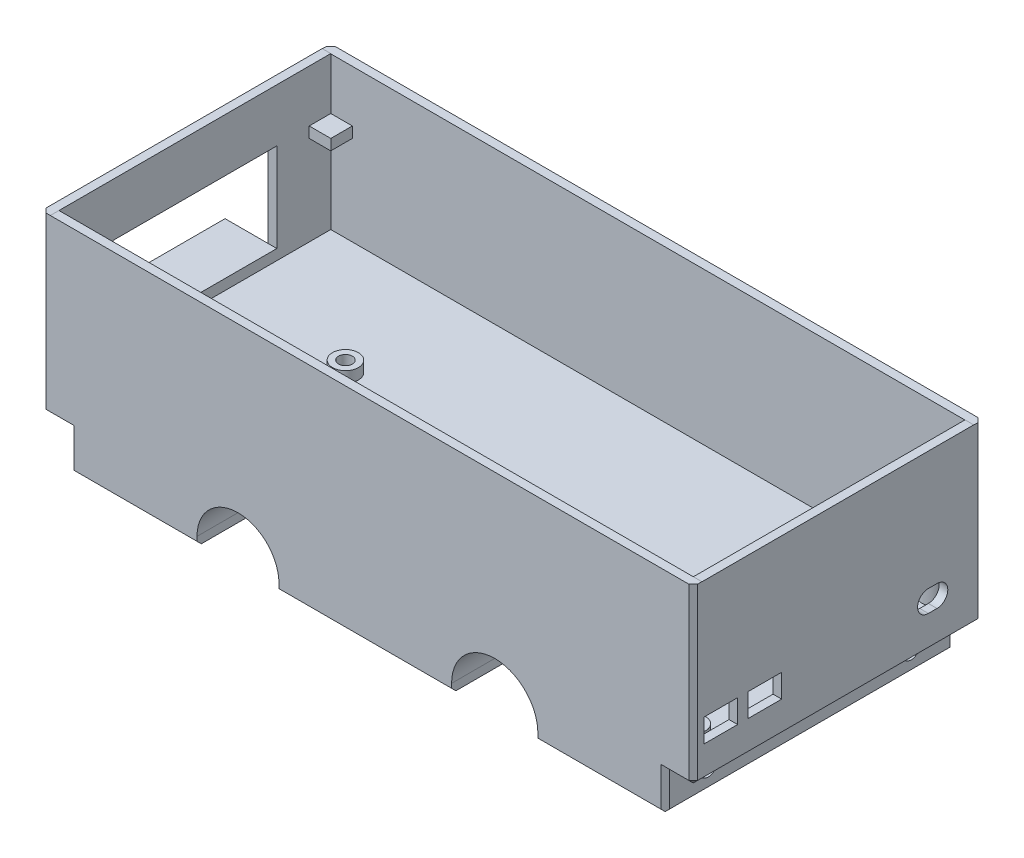
SolidWorks part; units mm, degrees
ref_plane "Ebene vorne" through (0, 0, 0) normal (0, 0, 1) x (1, 0, 0)
ref_plane "Ebene oben" through (0, 0, 0) normal (0, 1, 0) x (1, 0, 0)
ref_plane "Ebene rechts" through (0, 0, 0) normal (1, 0, 0) x (0, 0, -1)
sketch "Skizze1" plane through (0, 0, 0) normal (0, 0, 1) x (1, 0, 0)
  line L0 (13.4016, 0) -> (13.4016, -2)
  line L1 (13.4016, -2) -> (53.4016, -2)
  line L2 (53.4016, -2) -> (53.4016, 0)
  line L3 (51.4016, 0) -> (15.4882, 0)
  line L4 (-5.5984, 0) -> (-5.5984, -2)
  line L5 (-5.5984, -2) -> (-41.5984, -2)
  line L6 (-41.5984, -2) -> (-41.5984, 0)
  line L7 (-41.5984, 0) -> (-7.6851, 0)
  line L8 (73.4016, 0) -> (73.4016, -2)
  line L9 (73.4016, -2) -> (109.4016, -2)
  line L10 (75.4016, 0) -> (109.4016, 0)
  line L11 (109.4016, 0) -> (109.4016, -2)
  arc A0 (13.4016, 0) -> (-5.5984, 0) centre (3.9016, -3.1225) ccw
  arc A1 (73.4016, 0) -> (53.4016, 0) centre (63.4016, 0) ccw
  arc A2 (15.4882, 0) -> (-7.6851, 0) centre (3.9016, -3.1225) ccw
  arc A3 (75.4016, 0) -> (51.4016, 0) centre (63.4016, 0) ccw
  dimension "D2" = 10
  dimension "D3" = 12
  dimension "D4" = 10
  dimension "D5" = 12
  dimension "D6" = 40
  dimension "D7" = 2
  dimension "D8" = 2
  dimension "D9" = 2
  dimension "D10" = 2
  dimension "D11" = 2
  dimension "D12" = 2
  dimension "D13" = 36
  dimension "D14" = 2
  dimension "D15" = 36
extrude "Aufsatz-Linear austragen1" add sketch "Skizze1" along normal blind 67
sketch "Skizze3" plane through (0, 0, 0) normal (0, 1, 0) x (1, 0, 0)
  line L0 (109.4016, -67) -> (109.4016, 0) construction
  line L1 (-41.5984, 0) -> (109.4016, 0)
  line L2 (-41.5984, 0) -> (-41.5984, -2)
  line L3 (-41.5984, -2) -> (109.4016, -2)
  line L4 (109.4016, 0) -> (109.4016, -2)
  dimension "D1" = 2
extrude "Aufsatz-Linear austragen2" add sketch "Skizze3" along normal blind 47.3424
sketch "Skizze4" plane through (0, 0, 0) normal (0, 1, 0) x (1, 0, 0)
  line L0 (-7.6851, -67) -> (-41.5984, -67) construction
  line L1 (-41.5984, -2) -> (-39.5984, -2)
  line L2 (-41.5984, -2) -> (-41.5984, -67)
  line L3 (-41.5984, -67) -> (-39.5984, -67)
  line L4 (-39.5984, -2) -> (-39.5984, -67)
  dimension "D1" = 2
extrude "Aufsatz-Linear austragen3" add sketch "Skizze4" along normal blind 47.3981
sketch "Skizze6" plane through (0, 0, 0) normal (0, 1, 0) x (1, 0, 0)
  line L0 (109.4016, -67) -> (109.4016, -2) construction
  line L1 (-39.5984, -67) -> (109.4016, -67)
  line L2 (-39.5984, -67) -> (-39.5984, -65)
  line L3 (-39.5984, -65) -> (109.4016, -65)
  line L4 (109.4016, -67) -> (109.4016, -65)
  dimension "D1" = 2
extrude "Aufsatz-Linear austragen4" add sketch "Skizze6" along normal blind 47.401
sketch "Skizze7" plane through (0, 0, 0) normal (0, 1, 0) x (1, 0, 0)
  line L0 (75.4016, -2) -> (109.4016, -2) construction
  line L1 (109.4016, -65) -> (107.4016, -65)
  line L2 (109.4016, -65) -> (109.4016, -2)
  line L3 (109.4016, -2) -> (107.4016, -2)
  line L4 (107.4016, -65) -> (107.4016, -2)
  dimension "D1" = 2
extrude "Aufsatz-Linear austragen5" add sketch "Skizze7" along normal blind 47.3732
sketch "Skizze20" plane through (0, 0, 2) normal (0, 0, 1) x (1, 0, 0)
  line L0 (107.4016, 47.3424) -> (107.4016, 0) construction
  line L1 (107.4016, 12.0802) -> (-39.5984, 12.0802)
  line L2 (107.4016, 12.0802) -> (107.4016, 0)
  line L3 (107.4016, 0) -> (-39.5984, 0)
  line L4 (-39.5984, 12.0802) -> (-39.5984, 0)
extrude "Aufsatz-Linear austragen6" add sketch "Skizze20" along normal blind 63
sketch "Skizze8" plane through (0, 0, 67) normal (0, 0, 1) x (1, 0, 0)
  line L1 (-5.5984, 0) -> (13.4016, 0) construction
  line L2 (53.4016, 0) -> (73.4016, 0) construction
  line L3 (53.4016, -2) -> (53.4016, 0) construction
  line L4 (53.4016, 0) -> (73.4016, 0)
  line L5 (-5.5984, 0) -> (13.4016, 0)
  arc A2 (13.4016, 0) -> (-5.5984, 0) centre (3.9016, 0) ccw
  arc A3 (73.4016, 0) -> (53.4016, 0) centre (63.4016, 0) ccw
extrude "Schnitt-Linear austragen1" cut sketch "Skizze8" against normal through all
sketch "Skizze23" plane through (109.4016, 0, 0) normal (1, 0, 0) x (0, 0, -1)
  line L0 (-67, -2) -> (-67, 47.401) construction
  line L1 (-64.5, 19.9802) -> (-56.7, 19.9802)
  line L2 (-64.5, 19.9802) -> (-64.5, 14.5802)
  line L3 (-64.5, 14.5802) -> (-56.7, 14.5802)
  line L4 (-56.7, 19.9802) -> (-56.7, 14.5802)
  line L5 (-54.3, 19.9802) -> (-46.5, 19.9802)
  line L6 (-54.3, 19.9802) -> (-54.3, 14.5802)
  line L7 (-54.3, 14.5802) -> (-46.5, 14.5802)
  line L8 (-46.5, 19.9802) -> (-46.5, 14.5802)
  line L10 (-65, 12.0802) -> (-2, 12.0802) construction
  dimension "D1" = 2.4
  dimension "D2" = 2.5
  dimension "D3" = 7.8
  dimension "D4" = 7.8
  dimension "D5" = 2.5
  dimension "D6" = 5.4
  dimension "D7" = 5.4
extrude "Schnitt-Linear austragen12" cut sketch "Skizze23" against normal blind 47
sketch "Skizze26" plane through (109.4016, 0, 0) normal (1, 0, 0) x (0, 0, -1)
  line L0 (-67, -2) -> (-67, 47.401) construction
  line L1 (-67, -2) -> (0, -2) construction
  circle A0 centre (-57, 3) radius 2.05
  dimension "D1" = 10
  dimension "D2" = 5
  dimension "D3" = 4.1
extrude "Schnitt-Linear austragen13" cut sketch "Skizze26" against normal blind 38
sketch "Skizze28" plane through (109.4016, 0, 0) normal (1, 0, 0) x (0, 0, -1)
  line L0 (0, -2) -> (0, 47.3424) construction
  line L1 (-67, -2) -> (0, -2) construction
  circle A1 centre (-10, 3) radius 2.05
  dimension "D1" = 10
  dimension "D3" = 4.1
  dimension "D2" = 5
extrude "Schnitt-Linear austragen14" cut sketch "Skizze28" against normal blind 38 contours A1
sketch "Skizze29" plane through (-41.5984, 0, 0) normal (-1, 0, 0) x (0, 0, 1)
  line L1 (67, -2) -> (0, -2) construction
  line L2 (67, 47.3981) -> (67, -2) construction
  circle A1 centre (57, 3) radius 2.05
  dimension "D1" = 4.1
  dimension "D3" = 10
  dimension "D4" = 5
extrude "Schnitt-Linear austragen15" cut sketch "Skizze29" against normal blind 38 contours A1
sketch "Skizze31" plane through (-41.5984, 0, 0) normal (-1, 0, 0) x (0, 0, 1)
  line L0 (67, -2) -> (0, -2) construction
  line L1 (0, 47.3424) -> (0, -2) construction
  circle A0 centre (10, 3) radius 2.05
  dimension "D1" = 5
  dimension "D3" = 4.1
  dimension "D2" = 10
extrude "Schnitt-Linear austragen16" cut sketch "Skizze31" against normal blind 38
sketch "Skizze32" plane through (0, 12.0802, 0) normal (0, 1, 0) x (1, 0, 0)
  line L0 (-39.5984, -65) -> (-39.5984, -2) construction
  line L1 (109.4016, -65) -> (-39.5984, -65) construction
  circle A0 centre (-36.0984, -61.5) radius 3
  dimension "D1" = 3.5
  dimension "D3" = 6
  dimension "D2" = 3.5
extrude "Aufsatz-Linear austragen15" add sketch "Skizze32" along normal blind 23.29 contours A0
sketch "Skizze33" plane through (0, 12.0802, 0) normal (0, 1, 0) x (1, 0, 0)
  line L0 (107.4016, -2) -> (-39.5984, -2) construction
  line L1 (107.4016, -2) -> (107.4016, -65) construction
  circle A0 centre (103.9016, -5.5) radius 3
  dimension "D1" = 3.5
  dimension "D3" = 6
  dimension "D2" = 3.5
extrude "Aufsatz-Linear austragen16" add sketch "Skizze33" along normal blind 23.29
sketch "Skizze34" plane through (0, 35.3702, 0) normal (0, 1, 0) x (1, 0, 0)
  circle A0 centre (-36.0984, -61.5) radius 1.65
  dimension "D1" = 3.3
extrude "Schnitt-Linear austragen17" cut sketch "Skizze34" against normal blind 25
sketch "Skizze35" plane through (0, 35.3702, 0) normal (0, 1, 0) x (1, 0, 0)
  circle A0 centre (103.9016, -5.5) radius 1.65
  dimension "D1" = 3.3
extrude "Schnitt-Linear austragen18" cut sketch "Skizze35" against normal blind 25
sketch "Skizze37" plane through (109.4016, 0, 0) normal (1, 0, 0) x (0, 0, -1)
  line L0 (0, -2) -> (0, 47.3424) construction
  line L1 (-67, -2) -> (0, -2)
  line L2 (-67, -2) -> (-67, 7)
  line L3 (-67, 7) -> (0, 7)
  line L4 (0, -2) -> (0, 7)
  dimension "D1" = 9
extrude "Schnitt-Linear austragen20" cut sketch "Skizze37" against normal blind 6.5
sketch "Skizze38" plane through (-41.5984, 0, 0) normal (-1, 0, 0) x (0, 0, 1)
  line L0 (67, 47.3981) -> (67, -2) construction
  line L1 (0, -2) -> (67, -2)
  line L2 (0, -2) -> (0, 7)
  line L3 (0, 7) -> (67, 7)
  line L4 (67, -2) -> (67, 7)
  dimension "D1" = 9
extrude "Schnitt-Linear austragen21" cut sketch "Skizze38" against normal blind 6.5
chamfer "Fase2" distance 1 angle 45 16 edges at (106.1516, 7, 0) (102.9016, 2.5, 0) (109.4016, 27.1712, 0) (109.4016, 27.2005, 67) (102.9016, -2, 33.5) (102.9016, 2.5, 67) (106.1516, 7, 67) (109.4016, 7, 33.5) (-41.5984, 27.1991, 67) (-38.3484, 7, 67) (-35.0984, 2.5, 67) (-41.5984, 27.1712, 0) (-35.0984, -2, 33.5) (-35.0984, 2.5, 0) (-38.3484, 7, 0) (-41.5984, 7, 33.5)
chamfer "Fase13" distance 1 angle 45 6 edges at (87.6516, -2, 67) (33.4016, -2, 67) (-19.8484, -2, 67) (87.6516, -2, 0) (33.4016, -2, 0) (-19.8484, -2, 0)
sketch "Skizze40" plane through (0, 12.0802, 0) normal (0, 1, 0) x (1, 0, 0)
  line L0 (107.4016, -65) -> (-39.5984, -65) construction
  line L1 (107.4016, -65) -> (107.4016, -2) construction
  circle A0 centre (103.0916, -37.57) radius 2.85
  dimension "D1" = 5.7
  dimension "D3" = 4.31
  dimension "D2" = 27.43
extrude "Aufsatz-Linear austragen17" add sketch "Skizze40" along normal blind 1.5
sketch "Skizze41" plane through (0, 13.5802, 0) normal (0, 1, 0) x (1, 0, 0)
  line L0 (107.4016, -65) -> (107.4016, -2) construction
  line L1 (107.4016, -65) -> (-39.5984, -65) construction
  circle A0 centre (103.0916, -37.59) radius 1.65
  dimension "D1" = 3.3
  dimension "D2" = 4.31
  dimension "D3" = 27.41
extrude "Schnitt-Linear austragen23" cut sketch "Skizze41" against normal blind 5
sketch "Skizze42" plane through (0, 12.0802, 0) normal (0, 1, 0) x (1, 0, 0)
  line L0 (107.4016, -65) -> (107.4016, -2) construction
  line L1 (107.4016, -65) -> (-39.5984, -65) construction
  circle A0 centre (103.0916, -60.69) radius 2.85
  circle A1 centre (68.2016, -60.69) radius 2.85
  dimension "D1" = 5.7
  dimension "D2" = 5.7
  dimension "D3" = 4.31
  dimension "D4" = 4.31
  dimension "D5" = 4.31
  dimension "D6" = 39.2
extrude "Aufsatz-Linear austragen18" add sketch "Skizze42" along normal blind 1.5
sketch "Skizze43" plane through (109.4016, 0, 0) normal (1, 0, 0) x (0, 0, -1)
  line L0 (-12.5, 17.2802) -> (-10.5, 17.2802) construction
  line L1 (-12.5, 19.7802) -> (-10.5, 19.7802)
  line L2 (-12.5, 14.7802) -> (-10.5, 14.7802)
  line L3 (-46.5, 19.9802) -> (-54.3, 19.9802) construction
  line L5 (-46.5, 14.5802) -> (-46.5, 19.9802) construction
  arc A0 (-12.5, 19.7802) -> (-12.5, 14.7802) centre (-12.5, 17.2802) ccw
  arc A1 (-10.5, 14.7802) -> (-10.5, 19.7802) centre (-10.5, 17.2802) ccw
  point P2 (-11.5, 17.2802)
  point P7 (-15, 17.2802)
  point P8 (-8, 17.2802)
  dimension "D1" = 5
  dimension "D2" = 7
  dimension "D3" = 2.7
  dimension "D4" = 35
extrude "Schnitt-Linear austragen24" cut sketch "Skizze43" against normal blind 2
sketch "Skizze46" plane through (-39.5984, 0, 0) normal (1, 0, 0) x (0, 0, -1)
  line L0 (-2, 12.0802) -> (-2, 47.3424) construction
  line L1 (-7, 35.3702) -> (-2, 35.3702)
  line L2 (-7, 35.3702) -> (-7, 32.8702)
  line L3 (-7, 32.8702) -> (-2, 32.8702)
  line L4 (-2, 35.3702) -> (-2, 32.8702)
  line L5 (-65, 12.0802) -> (-2, 12.0802) construction
  dimension "D1" = 0
  dimension "D2" = 5
  dimension "D3" = 23.29
  dimension "D4" = 2.5
extrude "Aufsatz-Linear austragen21" add sketch "Skizze46" along normal blind 5
sketch "Skizze47" plane through (107.4016, 0, 0) normal (-1, 0, 0) x (0, 0, 1)
  line L0 (65, 47.3732) -> (65, 12.0802) construction
  line L1 (60, 35.3702) -> (65, 35.3702)
  line L2 (60, 35.3702) -> (60, 32.8702)
  line L3 (60, 32.8702) -> (65, 32.8702)
  line L4 (65, 35.3702) -> (65, 32.8702)
  line L5 (65, 12.0802) -> (2, 12.0802) construction
  dimension "D1" = 0
  dimension "D2" = 5
  dimension "D3" = 23.29
  dimension "D4" = 2.5
extrude "Aufsatz-Linear austragen22" add sketch "Skizze47" along normal blind 5
sketch "Skizze48" plane through (-41.5984, 0, 0) normal (-1, 0, 0) x (0, 0, 1)
  line L0 (1, 8) -> (66, 8) construction
  line L1 (14.5, 35.12) -> (52.5, 35.12)
  line L2 (14.5, 35.12) -> (14.5, 14.52)
  line L3 (14.5, 14.52) -> (52.5, 14.52)
  line L4 (52.5, 35.12) -> (52.5, 14.52)
  line L5 (1, 47.3424) -> (1, 8) construction
  dimension "D1" = 6.52
  dimension "D2" = 38
  dimension "D3" = 13.5
  dimension "D4" = 20.6
extrude "Schnitt-Linear austragen25" cut sketch "Skizze48" against normal blind 2
sketch "Skizze49" plane through (-41.5984, 0, 0) normal (-1, 0, 0) x (0, 0, 1)
  line L1 (14.5, 14.52) -> (52.5, 14.52)
  line L2 (14.5, 14.52) -> (14.5, 12.52)
  line L3 (14.5, 12.52) -> (52.5, 12.52)
  line L4 (52.5, 14.52) -> (52.5, 12.52)
  dimension "D1" = 2
extrude "Aufsatz-Linear austragen23" add sketch "Skizze49" along normal blind 10
sketch "Skizze51" plane through (0, 12.0802, 0) normal (0, 1, 0) x (1, 0, 0)
  line L0 (-39.5984, -65) -> (-39.5984, -2) construction
  line L1 (-39.5984, -52.5) -> (-41.5984, -52.5) construction
  circle A0 centre (-9.1984, -29) radius 3
  dimension "D1" = 6
  dimension "D2" = 30.4
  dimension "D3" = 23.5
extrude "Aufsatz-Linear austragen24" add sketch "Skizze51" along normal blind 2.5
sketch "Skizze52" plane through (0, 14.5802, 0) normal (0, 1, 0) x (1, 0, 0)
  line L0 (-41.5984, -2) -> (-41.5984, -67) construction
  line L1 (-39.5984, -52.5) -> (-41.5984, -52.5) construction
  circle A0 centre (-9.1984, -29) radius 1.6
  dimension "D1" = 3.2
  dimension "D2" = 32.4
  dimension "D3" = 23.5
extrude "Schnitt-Linear austragen26" cut sketch "Skizze52" against normal blind 15
